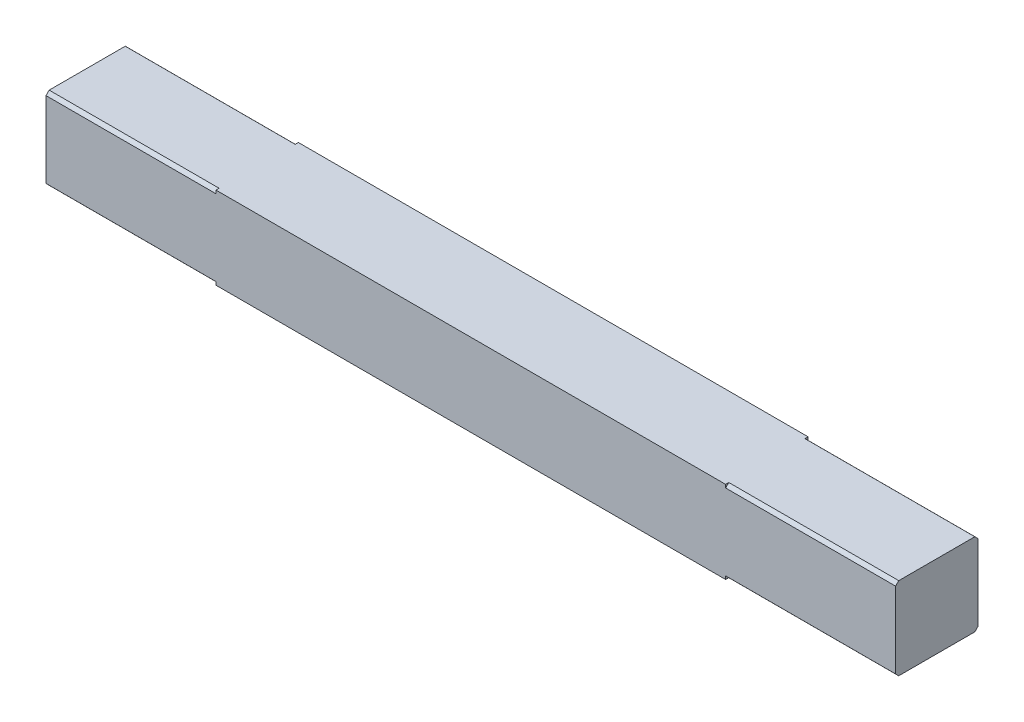
SolidWorks part; units mm, degrees
ref_plane "前视基准面" through (0, 0, 0) normal (0, 0, 1) x (1, 0, 0)
ref_plane "上视基准面" through (0, 0, 0) normal (0, 1, 0) x (1, 0, 0)
ref_plane "右视基准面" through (0, 0, 0) normal (1, 0, 0) x (0, 0, -1)
sketch "草图1" plane through (0, 0, 0) normal (0, 0, 1) x (1, 0, 0)
  line L1 (36.4593, 6.1281) -> (-13.5407, 6.1281)
  line L2 (36.4593, 6.1281) -> (36.4593, 1.2781)
  line L3 (36.4593, 1.2781) -> (-13.5407, 1.2781)
  line L4 (-13.5407, 6.1281) -> (-13.5407, 1.2781)
  line L5 (36.4593, 6.1281) -> (-13.5407, 1.2781) construction
  line L6 (36.4593, 1.2781) -> (-13.5407, 6.1281) construction
  point P0 (11.4593, 3.7031)
  dimension "D1" = 50
  dimension "D2" = 4.85
extrude "凸台-拉伸1" add sketch "草图1" along normal blind 4.85
sketch "草图2" plane through (-13.5407, 0, 0) normal (-1, 0, 0) x (0, 0, 1)
  circle A0 centre (2.425, 3.7031) radius 3.3
  dimension "D1" = 6.6
extrude "切除-拉伸1" cut sketch "草图2" against normal blind 10 flip side to cut
sketch "草图3" plane through (36.4593, 0, 0) normal (1, 0, 0) x (0, 0, -1)
  circle A0 centre (-2.425, 3.7031) radius 3.3
extrude "切除-拉伸2" cut sketch "草图3" against normal blind 10 flip side to cut
